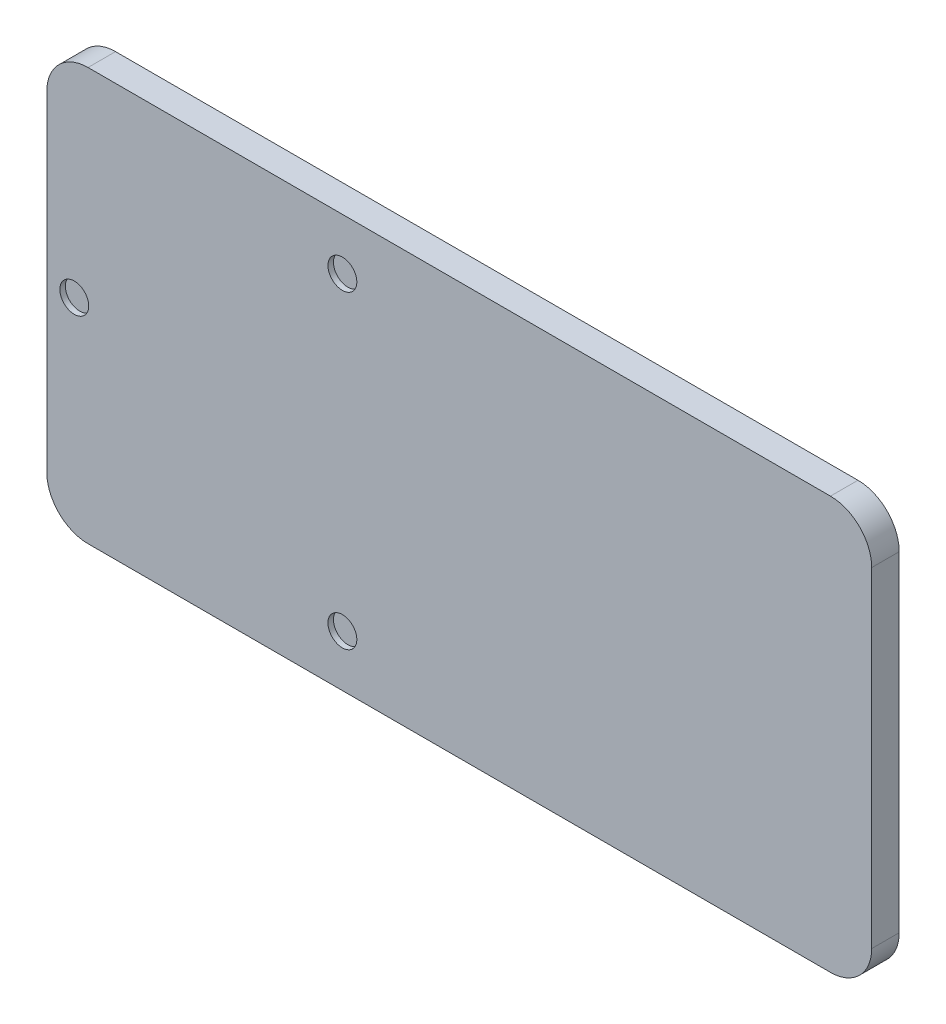
SolidWorks part; units mm, degrees
ref_plane "Płaszczyzna przednia" through (0, 0, 0) normal (0, 0, 1) x (1, 0, 0)
ref_plane "Płaszczyzna górna" through (0, 0, 0) normal (0, 1, 0) x (1, 0, 0)
ref_plane "Płaszczyzna prawa" through (0, 0, 0) normal (1, 0, 0) x (0, 0, -1)
sketch "Szkic1" plane through (0, 0, 0) normal (0, 0, 1) x (1, 0, 0)
  line L1 (-150, -75) -> (150, -75)
  line L2 (-150, -75) -> (-150, 75)
  line L3 (-150, 75) -> (150, 75)
  line L4 (150, -75) -> (150, 75)
  line L5 (-150, -75) -> (150, 75) construction
  line L6 (-150, 75) -> (150, -75) construction
  point P0 (0, 0)
  dimension "D1" = 150
  dimension "D2" = 300
extrude "Dodanie-wyciągnięcie1" add sketch "Szkic1" along normal blind 10
sketch "Szkic2" plane through (0, 0, 10) normal (0, 0, 1) x (1, 0, 0)
  line L0 (150, 75) -> (-150, 75) construction
  line L1 (-150, 75) -> (-150, -75) construction
  circle A0 centre (-140, 0) radius 5.25
  circle A1 centre (-42.5, 56.2917) radius 5.25
  circle A2 centre (-42.5, -56.2917) radius 5.25
  point P0 (-75, 0)
  point P13 (-75, 0)
  dimension "D2" = 10.5
  dimension "D3" = 65
  dimension "D1" = 75
  dimension "75" = 75
  dimension "D4" = 3
extrude "Wytnij-wyciągnięcie1" cut sketch "Szkic2" against normal blind 2
fillet "Zaokrąglenie1" radius 15 4 edges at (150, 75, 5) (150, -75, 5) (-150, -75, 5) (-150, 75, 5)
